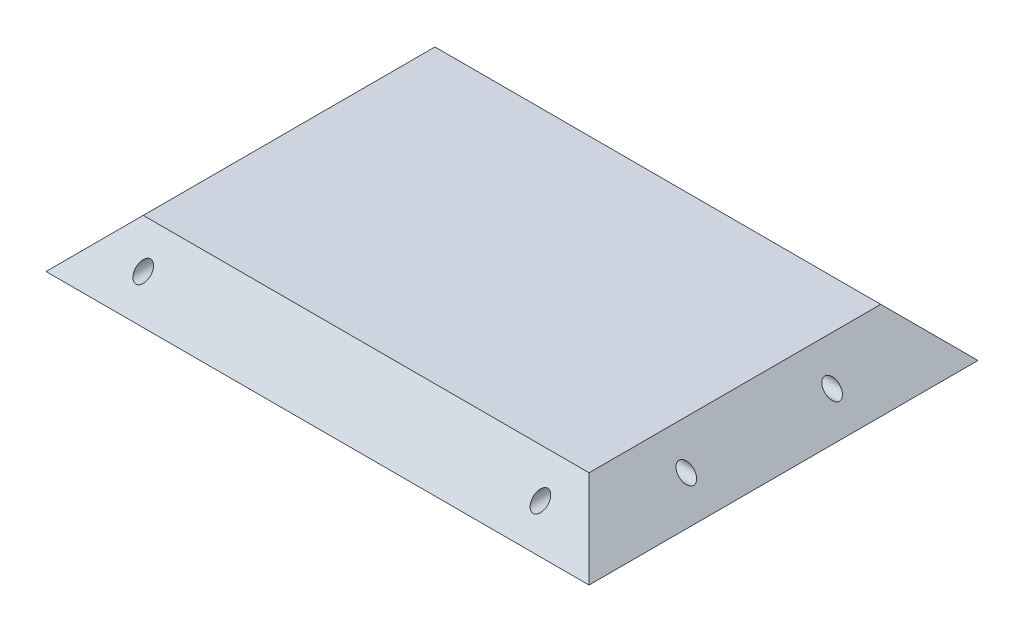
SolidWorks part; units mm, degrees
ref_plane "Спереди" through (0, 0, 0) normal (0, 0, 1) x (1, 0, 0)
ref_plane "Сверху" through (0, 0, 0) normal (0, 1, 0) x (1, 0, 0)
ref_plane "Справа" through (0, 0, 0) normal (1, 0, 0) x (0, 0, -1)
sketch "Эскиз1" plane through (0, 0, 0) normal (0, 1, 0) x (1, 0, 0)
  line L1 (-55.85, -40) -> (55.85, -40)
  line L2 (-55.85, -40) -> (-55.85, 40)
  line L3 (-55.85, 40) -> (55.85, 40)
  line L4 (55.85, -40) -> (55.85, 40)
  line L5 (-55.85, -40) -> (55.85, 40) construction
  line L6 (-55.85, 40) -> (55.85, -40) construction
  point P0 (0, 0)
  dimension "D1" = 111.7
  dimension "D2" = 80
ref_plane "Плоскость1" through (0, 10, 0) normal (0, 1, 0) x (1, 0, 0)
sketch "Эскиз2" plane through (0, 10, 0) normal (0, 1, 0) x (1, 0, 0)
  line L4 (-55.85, -40) -> (55.85, -40) construction
  line L5 (55.85, -40) -> (55.85, 40) construction
  line L6 (-55.85, 40) -> (55.85, 40) construction
  line L7 (-55.85, -40) -> (-55.85, 40) construction
  line L8 (45.85, 30) -> (-45.85, 30)
  line L9 (45.85, -30) -> (45.85, 30)
  line L10 (-45.85, 30) -> (-45.85, -30)
  line L11 (-45.85, -30) -> (45.85, -30)
  line L12 (45.85, 30) -> (-45.85, 30)
  line L13 (45.85, -30) -> (45.85, 30)
  line L14 (-45.85, 30) -> (-45.85, -30)
  line L15 (-45.85, -30) -> (45.85, -30)
  line L16 (-55.85, -40) -> (55.85, -40) construction
  line L17 (55.85, -40) -> (55.85, 40) construction
  line L18 (-55.85, 40) -> (55.85, 40) construction
  line L19 (-55.85, -40) -> (-55.85, 40) construction
  line L20 (-45.85, -30) -> (-45.85, -40) construction
  line L21 (-45.85, -30) -> (-55.85, -30) construction
  line L22 (-45.85, 30) -> (-45.85, 40) construction
  line L23 (-45.85, 30) -> (-55.85, 30) construction
  line L24 (45.85, -30) -> (45.85, -40) construction
  line L25 (45.85, -30) -> (55.85, -30) construction
  line L26 (45.85, 30) -> (45.85, 40) construction
  line L27 (45.85, 30) -> (55.85, 30) construction
  dimension "D1" = 10
loft "По сечениям1" add profiles "Эскиз1", "Эскиз2"
ref_plane "Плоскость2" through (0, 0, 40) normal (0, 0, 1) x (1, 0, 0)
sketch "Эскиз3" plane through (0, 0, 40) normal (0, 0, 1) x (1, 0, 0)
  line L0 (-55.85, 0) -> (-55.85, 10) construction
  line L1 (55.85, 0) -> (55.85, 10) construction
  line L2 (-55.85, 10) -> (55.85, 10) construction
  line L3 (45.85, 0) -> (45.85, 10) construction
  line L4 (-55.85, 0) -> (55.85, 0) construction
  line L5 (35.85, 10) -> (35.85, 5) construction
  line L6 (35.85, 5) -> (40.85, 5) construction
  line L7 (40.85, 5) -> (45.85, 5) construction
  line L8 (-55.85, 10) -> (55.85, 10) construction
  line L9 (0, 10) -> (0, 0) construction
  circle A0 centre (40.85, 5) radius 1.5
  circle A1 centre (-40.85, 5) radius 1.5
  dimension "D1" = 3
  dimension "D2" = 10
ref_plane "Плоскость3" through (0, 0, -40) normal (0, 0, -1) x (-1, 0, 0)
extrude "Вырез-Вытянуть1" cut sketch "Эскиз3" against normal blind 20 contours A0 | A1
mirror "Зеркальное отражение1" about plane through (0, 0, 0) normal (0, 0, 1) of "Вырез-Вытянуть1"
ref_plane "Плоскость4" through (55.85, 0, 0) normal (1, 0, 0) x (0, 0, -1)
sketch "Эскиз4" plane through (55.85, 0, 0) normal (1, 0, 0) x (0, 0, -1)
  line L0 (-40, 10) -> (-40, 0) construction
  line L1 (-40, 10) -> (40, 10) construction
  line L2 (40, 10) -> (40, 0) construction
  line L3 (-40, 10) -> (40, 10) construction
  line L4 (-20, 0) -> (-20, 10) construction
  line L5 (-40, 0) -> (40, 0) construction
  line L6 (-10, 10) -> (-10, 0) construction
  line L7 (-20, 5) -> (-10, 5) construction
  line L8 (0, 10) -> (0, 0) construction
  circle A0 centre (-15, 5) radius 1.5
  circle A1 centre (15, 5) radius 1.5
  dimension "D3" = 3
  dimension "D1" = 20
  dimension "D2" = 10
extrude "Вырез-Вытянуть2" cut sketch "Эскиз4" against normal blind 20 contours A1 | A0
mirror "Зеркальное отражение2" about plane through (0, 0, 0) normal (1, 0, 0) of "Вырез-Вытянуть2"
sketch "Эскиз5" plane through (0, 0, 0) normal (0, -1, 0) x (1, 0, 0)
  line L0 (-10.85, 25) -> (-40.85, 25)
  line L2 (-39.85, -5) -> (-39.85, 24)
  line L4 (-40.85, -5) -> (-40.85, 25)
  line L7 (-39.85, 24) -> (-10.85, 24)
  line L9 (-10.85, 24) -> (-10.85, 23.5)
  line L10 (-10.85, 23.5) -> (-9.85, 24.5)
  line L11 (-9.85, 24.5) -> (-10.85, 25.5)
  line L12 (-10.85, 25.5) -> (-10.85, 25)
  line L13 (-39.85, -5) -> (-39.35, -5)
  line L14 (-39.35, -5) -> (-40.35, -6)
  line L15 (-40.35, -6) -> (-41.35, -5)
  line L16 (-41.35, -5) -> (-40.85, -5)
  line L17 (-39.85, 24) -> (-39.85, 25) construction
  line L18 (-39.85, 24) -> (-40.85, 24) construction
  line L19 (-9.85, 24.5) -> (-39.85, 24.5) construction
  line L20 (-40.35, 24) -> (-40.35, -6) construction
  line L21 (-55.85, -40) -> (-55.85, 40) construction
  line L22 (-55.85, 40) -> (55.85, 40) construction
  point P17 (0, 0)
  point P22 (0, 0)
  dimension "D1" = 1
  dimension "D2" = 30
  dimension "D3" = 1
  dimension "D4" = 15
  dimension "D5" = 15
  dimension "D6" = 0.5
extrude "Вырез-Вытянуть3" cut sketch "Эскиз5" against normal blind 0.6
